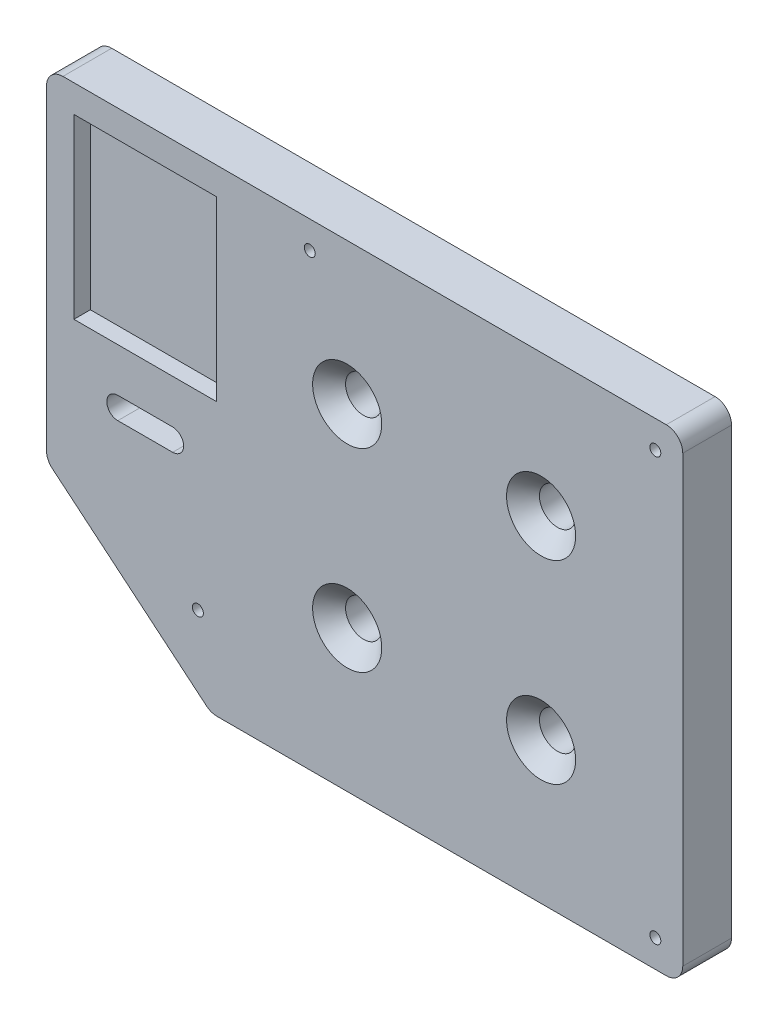
SolidWorks part; units mm, degrees
ref_plane "Front Plane" through (0, 0, 0) normal (0, 0, 1) x (1, 0, 0)
ref_plane "Top Plane" through (0, 0, 0) normal (0, 1, 0) x (1, 0, 0)
ref_plane "Right Plane" through (0, 0, 0) normal (1, 0, 0) x (0, 0, -1)
sketch "Sketch1" plane through (0, 0, 0) normal (0, 0, 1) x (1, 0, 0)
  circle A0 centre (0, 0) radius 37.5
  dimension "D1" = 75
extrude "Boss-Extrude1" add sketch "Sketch1" against normal blind 6
sketch "Sketch2" plane through (0, 0, -6) normal (0, 0, -1) x (-1, 0, 0)
  circle A0 centre (0, 0) radius 31.7
  dimension "D1" = 63.4
extrude "Cut-Extrude1" cut sketch "Sketch2" against normal up to surface (6 mm away) up to face at (37.5, 0, 0)
sketch "Sketch3" plane through (0, 0, 0) normal (0, 0, 1) x (1, 0, 0)
  line L1 (-42.5, -42.5) -> (42.5, -42.5)
  line L2 (-42.5, -42.5) -> (-42.5, 42.5)
  line L3 (-42.5, 42.5) -> (42.5, 42.5)
  line L4 (42.5, -42.5) -> (42.5, 42.5)
  line L5 (-42.5, -42.5) -> (42.5, 42.5) construction
  line L6 (-42.5, 42.5) -> (42.5, -42.5) construction
  point P0 (0, 0)
  dimension "D1" = 85
  dimension "D2" = 85
extrude "Boss-Extrude2" add sketch "Sketch3" along normal blind 25.4
fillet "Fillet2" radius 4 1 edges at (37.5, 0, 0)
sketch "Sketch4" plane through (0, 0, 25.4) normal (0, 0, 1) x (1, 0, 0)
  line L5 (-32.5, -32.5) -> (32.5, -32.5)
  line L6 (-32.5, -32.5) -> (-32.5, 32.5)
  line L7 (-32.5, 32.5) -> (32.5, 32.5)
  line L8 (32.5, -32.5) -> (32.5, 32.5)
  line L9 (-32.5, -32.5) -> (32.5, 32.5) construction
  line L10 (-32.5, 32.5) -> (32.5, -32.5) construction
  point P0 (0, 0)
  dimension "D1" = 65
extrude "Cut-Extrude2" cut sketch "Sketch4" against normal blind 16.51
hole_wizard "CSK for M6 Flat Head Machine Screw1" positions "Sketch6" profile "Sketch7" countersink size "M6" standard "ANSI Metric" end condition through all
sketch "Sketch6" plane through (0, 0, 8.89) normal (0, 0, 1) x (1, 0, 0)
  line L0 (0, 0) -> (63.2017, 0) construction
  line L4 (-17.6777, -17.6777) -> (36.1328, 36.1328) construction
  line L8 (37.119, -37.119) -> (-37.119, 37.119) construction
  line L9 (0, -42.5) -> (0, 42.5) construction
  line L10 (-42.5, -42.5) -> (42.5, -42.5) construction
  line L11 (42.5, 42.5) -> (-42.5, 42.5) construction
  circle A0 centre (0, 0) radius 25
  point P0 (-17.6777, 17.6777)
  point P2 (-17.6777, -17.6777)
  point P4 (17.6777, -17.6777)
  point P6 (17.6777, 17.6777)
  point P58 (0, 0)
  dimension "D1" = 50
  dimension "D2" = 45
  dimension "D3" = 90
sketch "Sketch7" plane through (-17.6777, 17.6777, 8.89) normal (1, 0, 0) x (0, -1, 0)
  line L0 (0, 0) -> (0, 14.89)
  line L1 (0, 14.89) -> (3.3, 14.89)
  line L2 (3.3, 14.89) -> (3.3, 3)
  line L3 (3.3, 3) -> (6.3, 0)
  line L5 (6.3, 0) -> (0, 0)
  line L6 (-3.3, 3) -> (-6.3, 0) construction
  line L11 (0, -6.35) -> (0, 107.95) construction
  dimension "Thru Hole Dia." = 6.6
  dimension "Thru Hole Depth" = 14.89
  dimension "Near C'Sink Dia." = 12.6
  dimension "Near C'Sink Angle" = 90
sketch "Sketch8" plane through (0, 0, 25.4) normal (0, 0, 1) x (1, 0, 0)
  line L1 (42.5, -42.5) -> (-42.5, -42.5)
  line L2 (42.5, -42.5) -> (42.5, 42.5)
  line L3 (42.5, 42.5) -> (-42.5, 42.5)
  line L4 (-42.5, -42.5) -> (-42.5, 42.5)
extrude "Cut-Extrude3" cut sketch "Sketch8" against normal up to surface (16.51 mm away) up to face at (-11.3777, 17.6777, 8.89)
sketch "Sketch9" plane through (0, 0, 8.89) normal (0, 0, 1) x (1, 0, 0)
  line L0 (42.5, 42.5) -> (-42.5, 42.5) construction
  line L1 (42.5, -42.5) -> (-42.5, -42.5)
  line L2 (42.5, -42.5) -> (42.5, 42.5)
  line L3 (42.5, 42.5) -> (-42.5, 42.5)
  line L4 (-42.5, -42.5) -> (-42.5, 42.5)
  line L5 (43.5, -43.5) -> (-72.5, -43.5)
  line L6 (43.5, -43.5) -> (43.5, 43.5)
  line L7 (43.5, 43.5) -> (-72.5, 43.5)
  line L8 (-72.5, -43.5) -> (-72.5, 43.5)
  dimension "D1" = 1
  dimension "D2" = 1
  dimension "D3" = 1
  dimension "D4" = 30
extrude "Boss-Extrude3" add sketch "Sketch9" against normal up to surface (8.89 mm away) up to face at (-41.5, 0, 0)
sketch "Sketch11" plane through (0, 0, 8.89) normal (0, 0, 1) x (1, 0, 0)
  line L9 (-67.5, 38.5) -> (-67.5, 6.15)
  line L17 (-67.5, 6.15) -> (-41.5, 6.15)
  line L18 (-41.5, 6.15) -> (-41.5, 38.5)
  line L20 (-41.5, 38.5) -> (-67.5, 38.5)
  line L21 (43.5, 43.5) -> (-72.5, 43.5) construction
  line L22 (-72.5, 43.5) -> (-72.5, -43.5) construction
  dimension "D1" = 5
  dimension "D2" = 5
  dimension "D3" = 32.35
  dimension "D4" = 26
sketch "Sketch12" plane through (0, 0, 8.89) normal (0, 0, 1) x (1, 0, 0)
  line L0 (-42.5, -43.5) -> (-72.5, -18.5)
  line L1 (-72.5, -43.5) -> (43.5, -43.5) construction
  line L2 (-72.5, 43.5) -> (-72.5, -43.5) construction
  line L3 (-72.5, -18.5) -> (-72.5, -43.5)
  line L4 (-72.5, -43.5) -> (-42.5, -43.5)
  dimension "D1" = 25
  dimension "D2" = 30
extrude "Cut-Extrude4" cut sketch "Sketch12" against normal up to surface (8.89 mm away) up to face at (-41.5, 0, 0)
extrude "Cut-Extrude5" cut sketch "Sketch11" against normal blind 3
sketch "Sketch13" plane through (0, 0, 8.89) normal (0, 0, 1) x (1, 0, 0)
  line L0 (-54.5, 6.15) -> (-54.5, -18.2474) construction
  line L1 (-67.5, 6.15) -> (-41.5, 6.15) construction
  line L2 (-49.5, -3.85) -> (-59.5, -3.85) construction
  line L3 (-49.5, -5.85) -> (-59.5, -5.85)
  line L4 (-49.5, -1.85) -> (-59.5, -1.85)
  arc A1 (-49.5, -5.85) -> (-49.5, -1.85) centre (-49.5, -3.85) ccw
  arc A2 (-59.5, -1.85) -> (-59.5, -5.85) centre (-59.5, -3.85) ccw
  point P6 (-54.5, -3.85)
  point P11 (0, 0)
  point P12 (-74.5, -8)
  dimension "D2" = 10
  dimension "D1" = 2
  dimension "D3" = 10
extrude "Cut-Extrude6" cut sketch "Sketch13" against normal up to surface (8.89 mm away) up to face at (-20.1, -3.7, 0)
sketch "Sketch14" plane through (0, 0, 8.89) normal (0, 0, 1) x (1, 0, 0)
  line L0 (43.5, 43.5) -> (-72.5, 43.5) construction
  line L1 (43.5, -43.5) -> (43.5, 43.5) construction
  line L2 (-42.5, -43.5) -> (43.5, -43.5) construction
  circle A0 centre (38.5, -38.5) radius 1
  circle A1 centre (38.5, 38.5) radius 1
  circle A2 centre (-24.5, 38.5) radius 1
  circle A3 centre (-44.8981, -28.4621) radius 1
  point P8 (0, 0)
  point P9 (0, 0)
  point P10 (40.1389, 39.9823)
  point P15 (38.5, -38.8043)
  point P18 (-28.5782, 38.5)
  dimension "D1" = 2
  dimension "D2" = 5
  dimension "D3" = 5
  dimension "D4" = 5
  dimension "D5" = 77
  dimension "D6" = 63
  dimension "D7" = 70
  dimension "D8" = 84
  dimension "D9" = 106.954
  dimension "D10" = 99.4887
extrude "Cut-Extrude7" cut sketch "Sketch14" against normal up to surface (8.89 mm away) up to face at (-54.5, -3.85, 0)
fillet "Fillet3" radius 3 5 edges at (43.5, -43.5, 4.445) (-42.5, -43.5, 4.445) (-72.5, -18.5, 4.445) (-72.5, 43.5, 4.445) (43.5, 43.5, 4.445)
